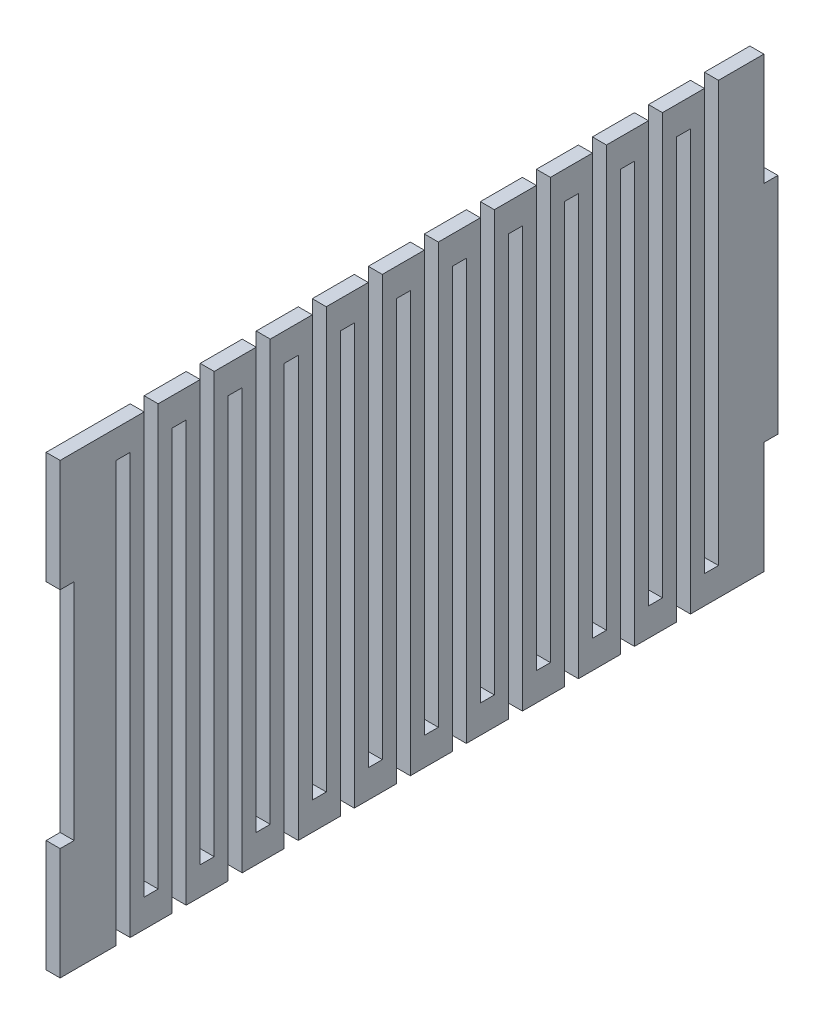
SolidWorks part; units mm, degrees
ref_plane "Front Plane" through (0, 0, 0) normal (0, 0, 1) x (1, 0, 0)
ref_plane "Top Plane" through (0, 0, 0) normal (0, 1, 0) x (1, 0, 0)
ref_plane "Right Plane" through (0, 0, 0) normal (1, 0, 0) x (0, 0, -1)
sketch "Sketch2" plane through (0, 0, 0) normal (1, 0, 0) x (0, 0, -1)
  line L0 (0, 76.2) -> (0, 101.6)
  line L1 (0, 76.2) -> (3.175, 76.2)
  line L3 (0, 25.4) -> (3.175, 25.4)
  line L5 (0, 25.4) -> (0, 0)
  line L6 (0, 101.6) -> (159.512, 101.6)
  line L7 (3.175, 76.2) -> (3.175, 25.4)
  line L8 (159.512, 101.6) -> (159.512, 76.2)
  line L9 (0, 0) -> (159.512, 0)
  line L10 (159.512, 76.2) -> (162.687, 76.2)
  line L11 (162.687, 76.2) -> (162.687, 25.4)
  line L12 (162.687, 25.4) -> (159.512, 25.4)
  line L13 (159.512, 25.4) -> (159.512, 0)
  line L14 (0, 101.6) -> (25.3583, 101.6)
  line L15 (28.575, 95.25) -> (25.4, 95.25)
  line L16 (28.575, 0) -> (28.575, 95.25)
  line L17 (25.4, 95.25) -> (25.4, 0)
  line L18 (31.75, 101.6) -> (31.75, 6.35)
  line L19 (31.75, 6.35) -> (34.925, 6.35)
  line L20 (34.925, 6.35) -> (34.925, 101.6)
  line L21 (41.275, 95.25) -> (38.1, 95.25)
  line L22 (41.275, 0) -> (41.275, 95.25)
  line L23 (38.1, 95.25) -> (38.1, 0)
  line L24 (44.45, 101.6) -> (44.45, 6.35)
  line L25 (44.45, 6.35) -> (47.625, 6.35)
  line L26 (47.625, 6.35) -> (47.625, 101.6)
  line L27 (53.975, 95.25) -> (50.8, 95.25)
  line L28 (53.975, 0) -> (53.975, 95.25)
  line L29 (50.8, 95.25) -> (50.8, 0)
  line L30 (57.15, 101.6) -> (57.15, 6.35)
  line L31 (57.15, 6.35) -> (60.325, 6.35)
  line L32 (60.325, 6.35) -> (60.325, 101.6)
  line L33 (66.675, 95.25) -> (63.5, 95.25)
  line L34 (66.675, 0) -> (66.675, 95.25)
  line L35 (63.5, 95.25) -> (63.5, 0)
  line L36 (69.85, 101.6) -> (69.85, 6.35)
  line L37 (69.85, 6.35) -> (73.025, 6.35)
  line L38 (73.025, 6.35) -> (73.025, 101.6)
  line L39 (79.375, 95.25) -> (76.2, 95.25)
  line L40 (79.375, 0) -> (79.375, 95.25)
  line L41 (76.2, 95.25) -> (76.2, 0)
  line L42 (82.55, 101.6) -> (82.55, 6.35)
  line L43 (82.55, 6.35) -> (85.725, 6.35)
  line L44 (85.725, 6.35) -> (85.725, 101.6)
  line L45 (92.075, 95.25) -> (88.9, 95.25)
  line L46 (92.075, 0) -> (92.075, 95.25)
  line L47 (88.9, 95.25) -> (88.9, 0)
  line L48 (95.25, 101.6) -> (95.25, 6.35)
  line L49 (95.25, 6.35) -> (98.425, 6.35)
  line L50 (98.425, 6.35) -> (98.425, 101.6)
  line L51 (104.775, 95.25) -> (101.6, 95.25)
  line L52 (104.775, 0) -> (104.775, 95.25)
  line L53 (101.6, 95.25) -> (101.6, 0)
  line L54 (107.95, 101.6) -> (107.95, 6.35)
  line L55 (107.95, 6.35) -> (111.125, 6.35)
  line L56 (111.125, 6.35) -> (111.125, 101.6)
  line L57 (117.475, 95.25) -> (114.3, 95.25)
  line L58 (117.475, 0) -> (117.475, 95.25)
  line L59 (114.3, 95.25) -> (114.3, 0)
  line L60 (120.65, 101.6) -> (120.65, 6.35)
  line L61 (120.65, 6.35) -> (123.825, 6.35)
  line L62 (123.825, 6.35) -> (123.825, 101.6)
  line L63 (130.175, 95.25) -> (127, 95.25)
  line L64 (130.175, 0) -> (130.175, 95.25)
  line L65 (127, 95.25) -> (127, 0)
  line L66 (133.35, 101.6) -> (133.35, 6.35)
  line L67 (133.35, 6.35) -> (136.525, 6.35)
  line L68 (136.525, 6.35) -> (136.525, 101.6)
  line L69 (142.875, 95.25) -> (139.7, 95.25)
  line L70 (142.875, 0) -> (142.875, 95.25)
  line L71 (139.7, 95.25) -> (139.7, 0)
  line L72 (146.05, 101.6) -> (146.05, 6.35)
  line L73 (146.05, 6.35) -> (149.225, 6.35)
  line L74 (149.225, 6.35) -> (149.225, 101.6)
  line L75 (15.875, 95.25) -> (12.7, 95.25)
  line L76 (15.875, 0) -> (15.875, 95.25)
  line L77 (12.7, 95.25) -> (12.7, 0)
  line L78 (19.05, 101.6) -> (19.05, 6.35)
  line L79 (19.05, 6.35) -> (22.225, 6.35)
  line L80 (22.225, 6.35) -> (22.225, 101.6)
  dimension "D1" = 10
  dimension "D2" = 2
extrude "Boss-Extrude2" add sketch "Sketch2" along normal blind 3.175 contours L80 L79 L78 L6 L0 L1 L7 L3 L5 L9 L77 L75 L76 L17 L15 L16 L23 L21 L22 L29 L27 L28 L35 L33 L34 L41 L39 L40 L47 L45 L46 L53 L51 L52 L59 L57 L58 L65 L63 L64 L71
